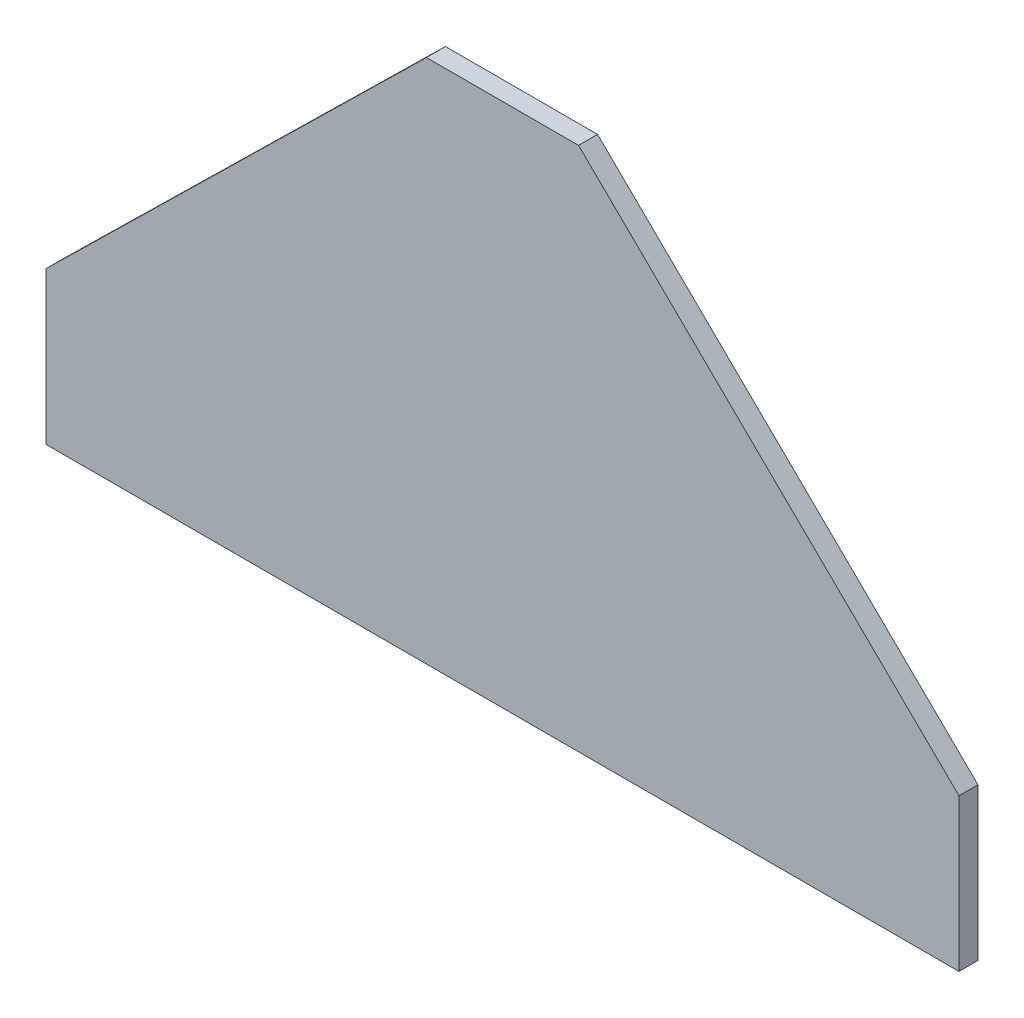
SolidWorks part; units mm, degrees
material "Plain Carbon Steel"
ref_plane "Front Plane" through (0, 0, 0) normal (0, 0, 1) x (1, 0, 0)
ref_plane "Top Plane" through (0, 0, 0) normal (0, 1, 0) x (1, 0, 0)
ref_plane "Right Plane" through (0, 0, 0) normal (1, 0, 0) x (0, 0, -1)
sketch "Sketch1" plane through (0, 0, 0) normal (0, 0, 1) x (1, 0, 0)
  line L0 (85.3601, 96.5667) -> (136.1601, 96.5667)
  line L1 (136.1601, 96.5667) -> (263.1601, -27.9765)
  line L2 (263.1601, -27.9765) -> (263.1601, -78.7765)
  line L3 (263.1601, -78.7765) -> (-41.6399, -78.7765)
  line L4 (-41.6399, -78.7765) -> (-41.6399, -27.9765)
  line L5 (-41.6399, -27.9765) -> (85.3601, 96.5667)
  dimension "D1" = 304.8
  dimension "D2" = 50.8
  dimension "D3" = 50.8
extrude "Boss-Extrude1" add sketch "Sketch1" along normal blind 6.35
